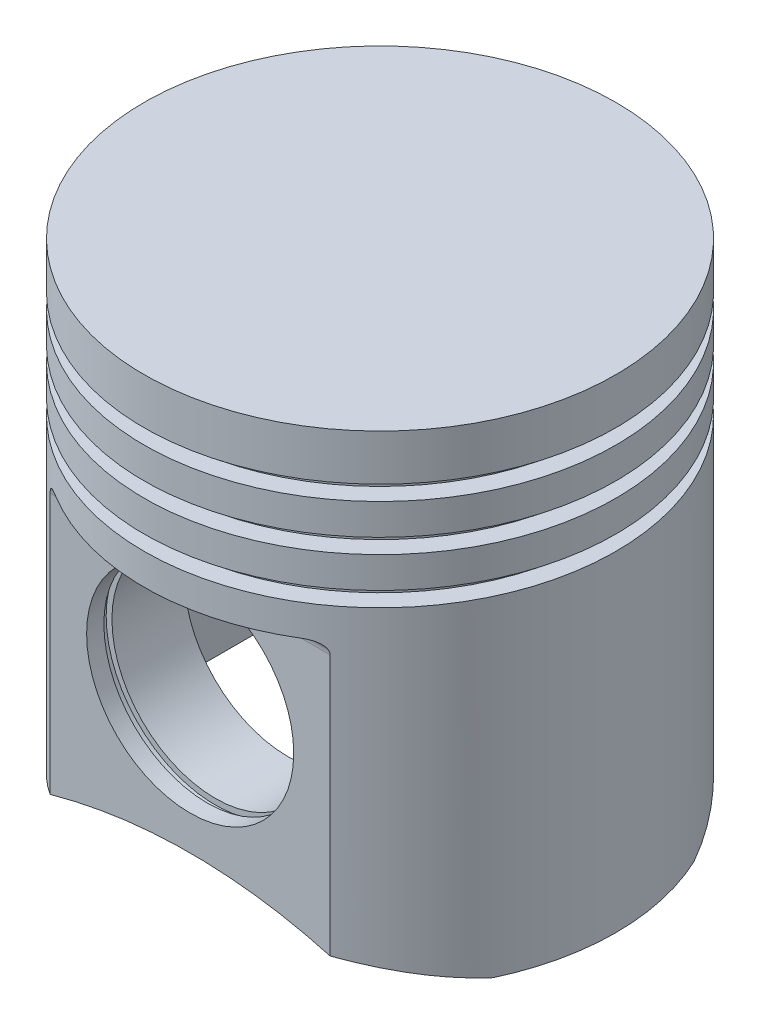
SolidWorks part; units mm, degrees
ref_plane "Спереди" through (0, 0, 0) normal (0, 0, 1) x (1, 0, 0)
ref_plane "Сверху" through (0, 0, 0) normal (0, 1, 0) x (1, 0, 0)
ref_plane "Справа" through (0, 0, 0) normal (1, 0, 0) x (0, 0, -1)
sketch "Эскиз13" plane through (0, 0, 0) normal (0, 1, 0) x (1, 0, 0)
  circle A0 centre (0, 0) radius 41
  dimension "D1" = 82
extrude "Бобышка-Вытянуть3" add sketch "Эскиз13" along normal mid plane 84
sketch "Эскиз16" plane through (0, -42, 0) normal (0, -1, 0) x (1, 0, 0)
  line L0 (-24.3311, 33) -> (24.3311, 33)
  line L1 (24.3311, -33) -> (-24.3311, -33)
  circle A2 centre (0, 0) radius 41 construction
  point P5 (0, 0)
  circle M6 centre (0, 0) radius 41
  dimension "D1" = 66
sketch "Эскиз14" plane through (0, 0, 0) normal (0, 0, 1) x (1, 0, 0)
  line L0 (560.6875, -10) -> (-560.6875, -10) construction
  line L1 (41, 42) -> (-41, 42) construction
  line L2 (-37.0945, -42) -> (37.0945, -42)
  line L4 (-41, -42) -> (41, -42) construction
  line L5 (0, 42) -> (0, -42) construction
  circle A0 centre (0, -10) radius 18
  arc A1 (37.0945, -42) -> (-37.0945, -42) centre (0, -124) ccw
  point P4 (0, 0)
  point P10 (0, -10)
  point P18 (0, -42)
  dimension "D2" = 36
  dimension "D3" = 90
  dimension "D1" = 52
  dimension "D4" = 76
extrude "Вырез-Вытянуть1" cut sketch "Эскиз14" against normal through all and the other way through all contours L2 A1 | A0
extrude "Вырез-Вытянуть3" cut sketch "Эскиз16" against normal blind 52 contours L0 M6 | L1 M6
sketch "Эскиз18" plane through (0, 0, 0) normal (0, 0, 1) x (1, 0, 0)
  line L0 (-29.7764, -6.3439) -> (-34.1544, -42)
  line L1 (-41, -42) -> (24.3311, -42) construction
  line L2 (29.7764, -6.3439) -> (34.1544, -42)
  line L3 (24.3311, -42) -> (41, -42) construction
  line L4 (41, 42) -> (-41, 42) construction
  line L5 (34.1544, -42) -> (-34.1544, -42)
  arc A0 (29.7764, -6.3439) -> (-29.7764, -6.3439) centre (0, -10) ccw
  dimension "D1" = 30
  dimension "D2" = 14
  dimension "D3" = 52
extrude "Вырез-Вытянуть4" cut sketch "Эскиз18" against normal mid plane 32
sketch "Эскиз20" plane through (0, 42, 0) normal (0, 1, 0) x (1, 0, 0)
  circle A0 centre (0, 0) radius 37.8
  circle M2 centre (0, 0) radius 41
  dimension "D1" = 75.6
extrude "Вырез-Вытянуть5" cut sketch "Эскиз20" against normal blind 2.6 from offset 8 contours A0 M2 offset against normal yes
pattern_linear "Линейный массив1" count 3 spacing 8 along (0, -1, 0) of "Вырез-Вытянуть5"
fillet "Скругление1" radius 2 2 edges at (0, 10, 33) (0, 10, -33)
sketch "Эскиз24" plane through (0, 0, 0) normal (1, 0, 0) x (0, 0, -1)
  line L0 (-30, -29) -> (-28.6, -29)
  line L5 (0, 503.8422) -> (0, -503.8422) construction
  line L6 (456.9583, -10) -> (-456.9583, -10) construction
  line L7 (41, 42) -> (-41, 42) construction
  line L8 (-30, -29) -> (-30, -10)
  line L9 (-30, -10) -> (-28.6, -10)
  line L10 (-28.6, -10) -> (-28.6, -29)
  line L11 (-33, 8) -> (-33, -37.3513) construction
  line L12 (28.6, -10) -> (28.6, -29)
  line L13 (30, -10) -> (28.6, -10)
  line L14 (30, -29) -> (30, -10)
  line L15 (30, -29) -> (28.6, -29)
  point P10 (0, 0)
  point P14 (0, -10)
  dimension "D1" = 1.4
  dimension "D2" = 3
  dimension "D3" = 52
  dimension "D4" = 38
revolve "Вырез-Повернуть3" cut sketch "Эскиз24" angle 360 about L6
